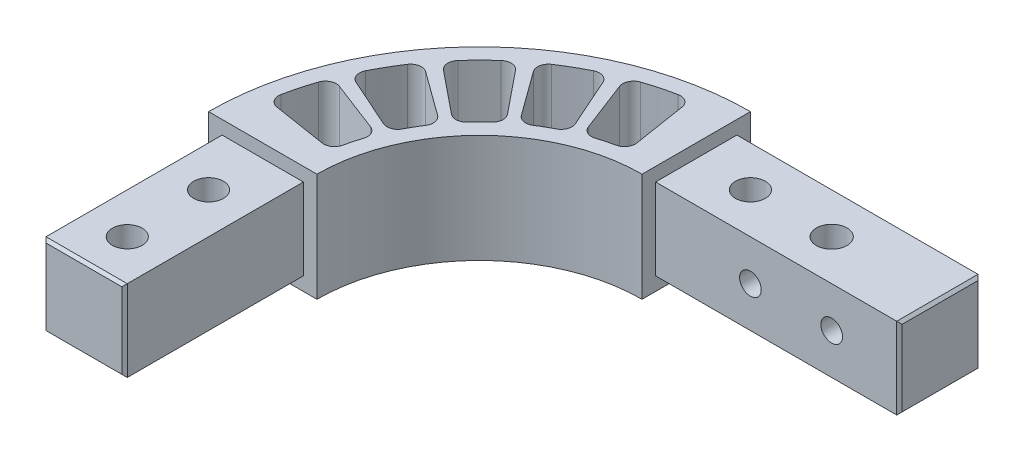
SolidWorks part; units mm, degrees
material "PA Type 6"
ref_plane "Front Plane" through (0, 0, 0) normal (0, 0, 1) x (1, 0, 0)
ref_plane "Top Plane" through (0, 0, 0) normal (0, 1, 0) x (1, 0, 0)
ref_plane "Right Plane" through (0, 0, 0) normal (1, 0, 0) x (0, 0, -1)
sketch "Sketch1" plane through (0, 0, 0) normal (0, 1, 0) x (1, 0, 0)
  line L0 (0, 68.9384) -> (0, -62.3869) construction
  line L1 (-91.3383, 0) -> (61.1848, 0) construction
  line L2 (0, 50) -> (0, 30)
  line L3 (-50, 0) -> (-30, 0)
  arc A0 (0, 50) -> (-50, 0) centre (0, 0) ccw
  arc A1 (0, 30) -> (-30, 0) centre (0, 0) ccw
  dimension "D1" = 100
  dimension "D2" = 60
extrude "Boss-Extrude1" add sketch "Sketch1" along normal blind 20
sketch "Sketch2" plane through (0, 0, 0) normal (0, 0, 1) x (1, 0, 0)
  line L0 (-50, 20) -> (-30, 0) construction
  line L1 (-30, 20) -> (-50, 0) construction
  line L3 (-47.5, 2.5) -> (-32.5, 2.5)
  line L4 (-47.5, 2.5) -> (-47.5, 17.5)
  line L5 (-47.5, 17.5) -> (-32.5, 17.5)
  line L6 (-32.5, 2.5) -> (-32.5, 17.5)
  line L7 (-47.5, 2.5) -> (-32.5, 17.5) construction
  line L8 (-47.5, 17.5) -> (-32.5, 2.5) construction
  point P8 (-40, 10)
  dimension "D1" = 15
extrude "Boss-Extrude2" add sketch "Sketch2" along normal blind 33
sketch "Sketch3" plane through (0, 0, 0) normal (1, 0, 0) x (0, 0, -1)
  line L0 (30, 20) -> (50, 0) construction
  line L1 (50, 20) -> (30, 0) construction
  line L3 (32.5, 2.5) -> (47.5, 2.5)
  line L4 (32.5, 2.5) -> (32.5, 17.5)
  line L5 (32.5, 17.5) -> (47.5, 17.5)
  line L6 (47.5, 2.5) -> (47.5, 17.5)
  line L7 (32.5, 2.5) -> (47.5, 17.5) construction
  line L8 (32.5, 17.5) -> (47.5, 2.5) construction
  point P8 (40, 10)
  dimension "D1" = 15
extrude "Boss-Extrude3" add sketch "Sketch3" along normal blind 45
sketch "Sketch4" plane through (0, 17.5, 0) normal (0, 1, 0) x (1, 0, 0)
  line L0 (-40, -33) -> (-40, 35.2645) construction
  line L1 (-32.5, -33) -> (-47.5, -33) construction
  line L2 (45, 40) -> (-33.6473, 40) construction
  line L3 (45, 47.5) -> (45, 32.5) construction
  line L4 (-57.4384, 0) -> (0, 0) construction
  line L5 (0, 0) -> (0, 52.2274) construction
  line L6 (10, 0) -> (10, 52.2274) construction
  line L7 (-57.4384, -10) -> (0, -10) construction
  line L8 (-57.4384, -25) -> (0, -25) construction
  line L9 (25, 0) -> (25, 52.2274) construction
  circle A0 centre (10, 40) radius 2.75
  circle A1 centre (25, 40) radius 2.825
  circle A2 centre (-40, -10) radius 2.75
  circle A3 centre (-40, -25) radius 2.75
  dimension "D5" = 5.5
  dimension "D6" = 5.5
  dimension "D7" = 5.65
  dimension "D8" = 5.5
  dimension "D1" = 10
  dimension "D2" = 10
  dimension "D3" = 15
  dimension "D4" = 15
extrude "Cut-Extrude1" cut sketch "Sketch4" against normal through all
sketch "Sketch5" plane through (0, 20, 0) normal (0, 1, 0) x (1, 0, 0)
  line L0 (0, 50) -> (0, 30) construction
  line L1 (-50, 0) -> (-30, 0) construction
  line L2 (0, 0) -> (-66.0694, 0) construction
  line L3 (0, 0) -> (-45.0318, 45.0318) construction
  line L4 (0, 0) -> (-37.5068, 46.317) construction
  line L5 (0, 0) -> (-47.2892, 38.2941) construction
  line L6 (-21.9902, 27.1557) -> (-28.2914, 34.937)
  line L7 (-27.1557, 21.9902) -> (-34.937, 28.2914)
  line L8 (-20.5389, 28.2693) -> (-26.4242, 36.3698)
  line L9 (-14.2125, 31.9218) -> (-18.2851, 41.0689)
  line L10 (-12.5224, 32.6219) -> (-16.1106, 41.9696)
  line L11 (-5.4663, 34.5126) -> (-7.0326, 44.4021)
  line L14 (-3.6525, 34.7514) -> (-4.6991, 44.7093) [skipped]
  line L15 (3.6525, 34.7514) -> (4.6991, 44.7093) [skipped]
  line L16 (-31.9218, 14.2125) -> (-41.0689, 18.2851)
  line L17 (-28.2693, 20.5389) -> (-36.3698, 26.4242)
  line L18 (-34.5126, 5.4663) -> (-44.4021, 7.0326)
  line L19 (-32.6219, 12.5224) -> (-41.9696, 16.1106)
  line L22 (-34.7514, -3.6525) -> (-44.7093, -4.6991) [skipped]
  line L23 (-34.7514, 3.6525) -> (-44.7093, 4.6991) [skipped]
  arc A0 (0, 30) -> (-30, 0) centre (0, 0) ccw construction
  arc A1 (0, 50) -> (-50, 0) centre (0, 0) ccw construction
  arc A3 (-31.1722, 35.1752) -> (-35.1752, 31.1722) centre (0, 0) ccw
  arc A4 (-21.9902, 27.1557) -> (-22.1991, 24.4172) centre (-23.5445, 25.897) cw
  arc A5 (-22.1991, 24.4172) -> (-24.4172, 22.1991) centre (0, 0) ccw
  arc A6 (-27.1557, 21.9902) -> (-24.4172, 22.1991) centre (-25.897, 23.5445) ccw
  arc A7 (-34.937, 28.2914) -> (-35.1752, 31.1722) centre (-33.6784, 29.8457) cw
  arc A8 (-28.2914, 34.937) -> (-31.1722, 35.1752) centre (-29.8457, 33.6784) ccw
  arc A9 (-26.4242, 36.3698) -> (-25.9087, 39.214) centre (-24.8062, 37.5454) cw
  arc A10 (-20.5389, 28.2693) -> (-17.8396, 27.7623) centre (-18.9208, 29.4449) ccw
  arc A11 (-21.006, 42.0446) -> (-25.9087, 39.214) centre (0, 0) ccw
  arc A12 (-18.2851, 41.0689) -> (-21.006, 42.0446) centre (-20.1122, 40.2555) ccw
  arc A13 (-14.2125, 31.9218) -> (-15.1231, 29.3308) centre (-16.0396, 31.1084) cw
  arc A14 (-15.1231, 29.3308) -> (-17.8396, 27.7623) centre (0, 0) ccw
  arc A15 (-16.1106, 41.9696) -> (-14.8765, 44.5835) centre (-14.2435, 42.6863) cw
  arc A16 (-12.5224, 32.6219) -> (-10.0464, 31.4336) centre (-10.6552, 33.3387) ccw
  arc A17 (-9.4083, 46.0487) -> (-14.8765, 44.5835) centre (0, 0) ccw
  arc A18 (-7.0326, 44.4021) -> (-9.4083, 46.0487) centre (-9.008, 44.0892) ccw
  arc A19 (-5.4663, 34.5126) -> (-7.0164, 32.2455) centre (-7.4416, 34.1997) cw
  arc A20 (-7.0164, 32.2455) -> (-10.0464, 31.4336) centre (0, 0) ccw
  arc A27 (-4.6991, 44.7093) -> (-2.8305, 46.9147) centre (-2.7101, 44.9183) cw [skipped]
  arc A28 (2.8305, 46.9147) -> (-2.8305, 46.9147) centre (0, 0) ccw [skipped]
  arc A29 (4.6991, 44.7093) -> (2.8305, 46.9147) centre (2.7101, 44.9183) ccw [skipped]
  arc A30 (3.6525, 34.7514) -> (1.5684, 32.9627) centre (1.6635, 34.9604) cw [skipped]
  arc A31 (1.5684, 32.9627) -> (-1.5684, 32.9627) centre (0, 0) ccw [skipped]
  arc A32 (-3.6525, 34.7514) -> (-1.5684, 32.9627) centre (-1.6635, 34.9604) ccw [skipped]
  arc A33 (-41.0689, 18.2851) -> (-42.0446, 21.006) centre (-40.2555, 20.1122) cw
  arc A34 (-31.9218, 14.2125) -> (-29.3308, 15.1231) centre (-31.1084, 16.0396) ccw
  arc A35 (-39.214, 25.9087) -> (-42.0446, 21.006) centre (0, 0) ccw
  arc A36 (-36.3698, 26.4242) -> (-39.214, 25.9087) centre (-37.5454, 24.8062) ccw
  arc A37 (-28.2693, 20.5389) -> (-27.7623, 17.8396) centre (-29.4449, 18.9208) cw
  arc A38 (-27.7623, 17.8396) -> (-29.3308, 15.1231) centre (0, 0) ccw
  arc A39 (-44.4021, 7.0326) -> (-46.0487, 9.4083) centre (-44.0892, 9.008) cw
  arc A40 (-34.5126, 5.4663) -> (-32.2455, 7.0164) centre (-34.1997, 7.4416) ccw
  arc A41 (-44.5835, 14.8765) -> (-46.0487, 9.4083) centre (0, 0) ccw
  arc A42 (-41.9696, 16.1106) -> (-44.5835, 14.8765) centre (-42.6863, 14.2435) ccw
  arc A43 (-32.6219, 12.5224) -> (-31.4336, 10.0464) centre (-33.3387, 10.6552) cw
  arc A44 (-31.4336, 10.0464) -> (-32.2455, 7.0164) centre (0, 0) ccw
  arc A51 (-44.7093, -4.6991) -> (-46.9147, -2.8305) centre (-44.9183, -2.7101) cw [skipped]
  arc A52 (-46.9147, 2.8305) -> (-46.9147, -2.8305) centre (0, 0) ccw [skipped]
  arc A53 (-44.7093, 4.6991) -> (-46.9147, 2.8305) centre (-44.9183, 2.7101) ccw [skipped]
  arc A54 (-34.7514, 3.6525) -> (-32.9627, 1.5684) centre (-34.9604, 1.6635) cw [skipped]
  arc A55 (-32.9627, 1.5684) -> (-32.9627, -1.5684) centre (0, 0) ccw [skipped]
  arc A56 (-34.7514, -3.6525) -> (-32.9627, -1.5684) centre (-34.9604, -1.6635) ccw [skipped]
  point P19 (-20.7676, 25.6458)
  point P22 (-25.6458, 20.7676)
  point P25 (-36.5259, 29.5781)
  point P28 (-29.5781, 36.5259)
  point P67 (0, 0)
  point P113 (0, 0)
  dimension "D1" = 45
  dimension "D2" = 3
  dimension "D3" = 33
  dimension "D6" = 2
  dimension "D4" = 6
  dimension "D5" = 6
  dimension "D7" = 4
  dimension "D8" = 4
extrude "Cut-Extrude2" cut sketch "Sketch5" against normal through all
chamfer "Chamfer1" distance 0.5 angle 45 8 edges at (45, 2.5, -40) (45, 10, -32.5) (45, 17.5, -40) (45, 10, -47.5) (-40, 2.5, 33) (-47.5, 10, 33) (-40, 17.5, 33) (-32.5, 10, 33)
sketch "Sketch6" plane through (0, 0, -47.5) normal (0, 0, -1) x (-1, 0, 0)
  line L0 (-44.5, 10) -> (0, 10) construction
  line L1 (-44.5, 17.5) -> (-44.5, 2.5) construction
  line L2 (0, 20) -> (0, 0) construction
  circle A0 centre (-17.5, 10) radius 2
  circle A1 centre (-32.5, 10) radius 2
  dimension "D2" = 17.5
  dimension "D3" = 4
  dimension "D4" = 4
  dimension "D1" = 15
extrude "Cut-Extrude3" cut sketch "Sketch6" against normal blind 20
